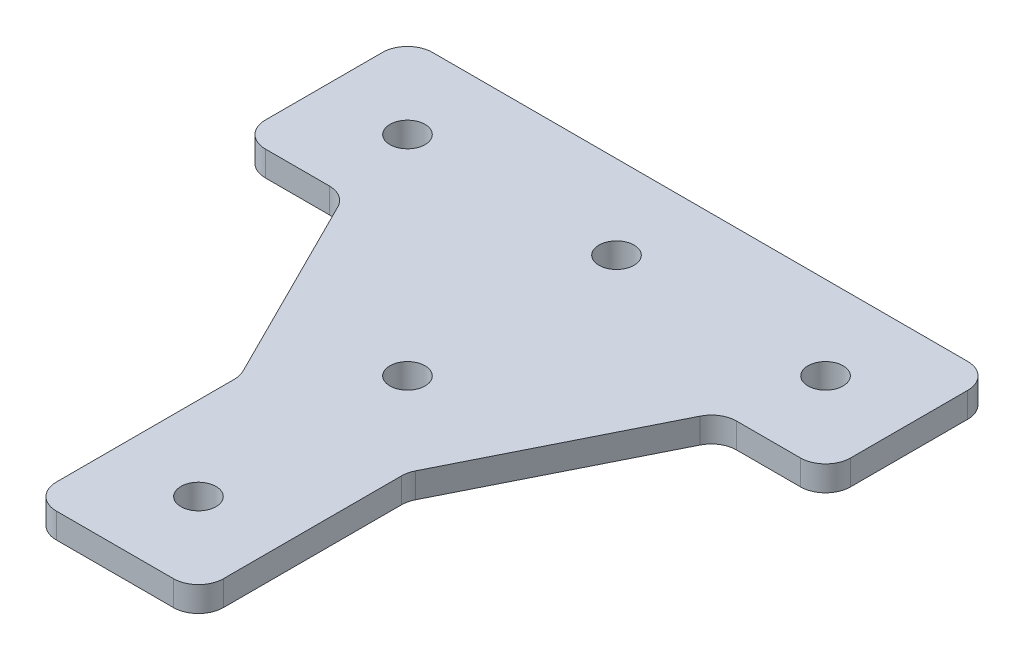
SolidWorks part; units mm, degrees
material "A-玻璃纤维"
ref_plane "前视基准面" through (0, 0, 0) normal (0, 0, 1) x (1, 0, 0)
ref_plane "上视基准面" through (0, 0, 0) normal (0, 1, 0) x (1, 0, 0)
ref_plane "右视基准面" through (0, 0, 0) normal (1, 0, 0) x (0, 0, -1)
sketch "草图1" plane through (0, 0, 0) normal (0, 1, 0) x (1, 0, 0)
  line L0 (-43.2884, 0) -> (46.6978, 0) construction
  line L1 (0, 0) -> (0, -50) construction
  line L2 (35, 10) -> (-35, 10)
  line L3 (-35, 10) -> (-35, -10)
  line L4 (-35, -10) -> (-10, -10)
  line L5 (-10, -10) -> (-10, -60)
  line L6 (-10, -60) -> (10, -60)
  line L7 (10, -60) -> (10, -10)
  line L8 (10, -10) -> (35, -10)
  line L9 (35, -10) -> (35, 10)
  line L10 (-22.5, -10) -> (-10, -35)
  line L11 (22.5, -10) -> (10, -35)
  circle A0 centre (0, 0) radius 2.1
  circle A1 centre (25, 0) radius 2.1
  circle A2 centre (-25, 0) radius 2.1
  circle A3 centre (0, -25) radius 2.1
  circle A4 centre (0, -50) radius 2.1
  dimension "D1" = 4.2
  dimension "D2" = 25
  dimension "D3" = 25
  dimension "D4" = 25
  dimension "D5" = 25
  dimension "D7" = 10
  dimension "D6" = 20
  dimension "D8" = 10
  dimension "D9" = 20
  dimension "D10" = 10
extrude "凸台-拉伸1" add sketch "草图1" along normal blind 3 contours L8 L9 L2 L3 L4 L5 L6 L7 A4 A3 A2 A1 A0 | L4 L10 L5 | L11 L8 L7
fillet "圆角1" radius 3 10 edges at (10, 1.5, 35) (10, 1.5, 60) (-10, 1.5, 60) (-10, 1.5, 35) (-22.5, 1.5, 10) (-35, 1.5, 10) (35, 1.5, -10) (35, 1.5, 10) (22.5, 1.5, 10) (-35, 1.5, -10)
